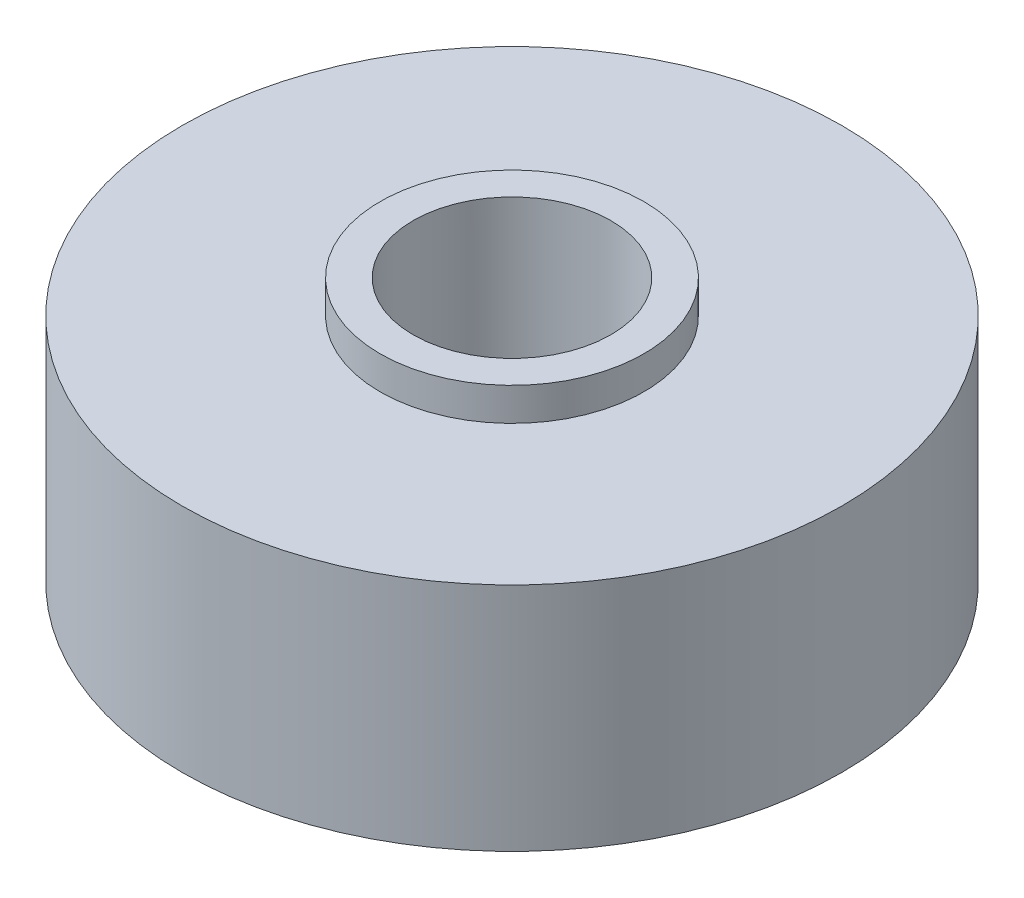
SolidWorks part; units mm, degrees
ref_plane "Front Plane" through (0, 0, 0) normal (0, 0, 1) x (1, 0, 0)
ref_plane "Top Plane" through (0, 0, 0) normal (0, 1, 0) x (1, 0, 0)
ref_plane "Right Plane" through (0, 0, 0) normal (1, 0, 0) x (0, 0, -1)
sketch "Sketch1" plane through (0, 0, 0) normal (0, 1, 0) x (1, 0, 0)
  circle A0 centre (0, 0) radius 10
  dimension "D1" = 20
extrude "Boss-Extrude1" add sketch "Sketch1" along normal blind 7
sketch "Sketch2" plane through (0, 7, 0) normal (0, 1, 0) x (1, 0, 0)
  circle A0 centre (0, 0) radius 3
  circle A1 centre (0, 0) radius 4
  dimension "D1" = 6
  dimension "D2" = 8
extrude "Boss-Extrude2" add sketch "Sketch2" along normal blind 1
sketch "Sketch4" plane through (0, 7, 0) normal (0, 1, 0) x (1, 0, 0)
  circle A1 centre (0, 0) radius 3
extrude "Cut-Extrude2" cut sketch "Sketch4" against normal blind 8
sketch "Sketch5" plane through (0, 0, 0) normal (0, -1, 0) x (1, 0, 0)
  circle A0 centre (0, 0) radius 4
  circle A1 centre (0, 0) radius 3
extrude "Boss-Extrude3" add sketch "Sketch5" along normal blind 1
